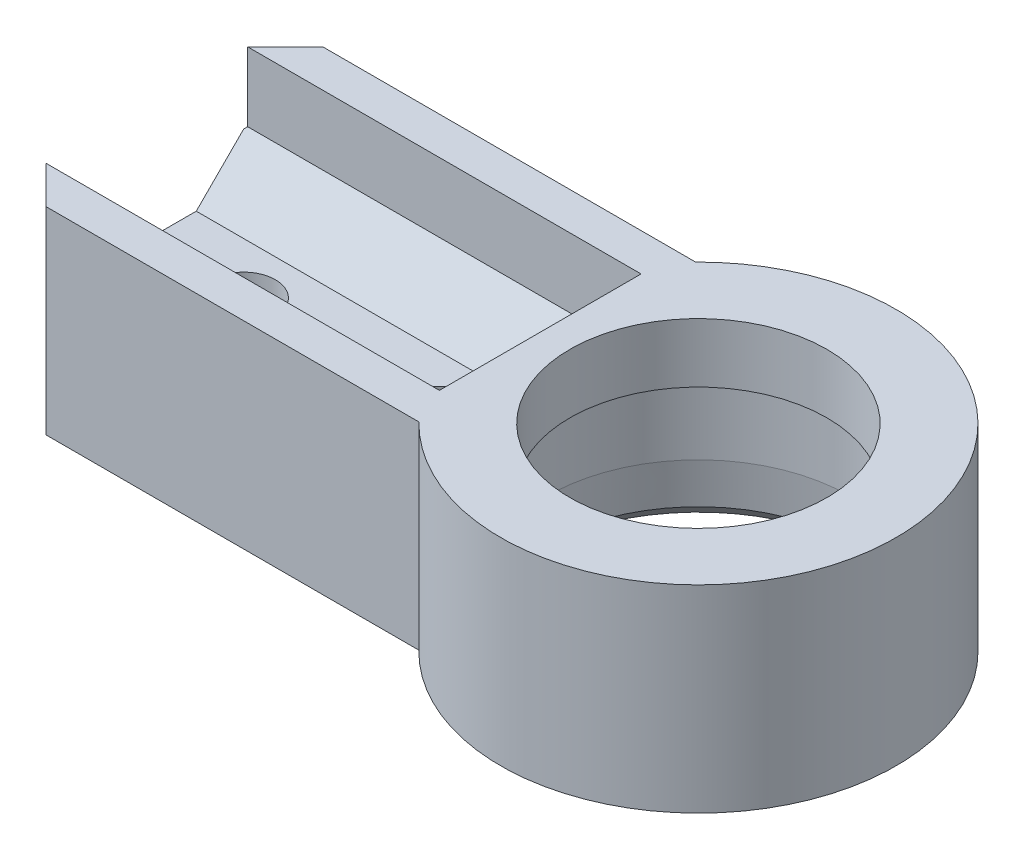
SolidWorks part; units mm, degrees
ref_plane "Plan de face" through (0, 0, 0) normal (0, 0, 1) x (1, 0, 0)
ref_plane "Plan de dessus" through (0, 0, 0) normal (0, 1, 0) x (1, 0, 0)
ref_plane "Plan de droite" through (0, 0, 0) normal (1, 0, 0) x (0, 0, -1)
sketch "Esquisse1" plane through (0, 0, 0) normal (0, 1, 0) x (1, 0, 0)
  line L1 (-28, -7) -> (-7.1414, -7)
  line L2 (-28, -7) -> (-28, 7)
  line L3 (-28, 7) -> (-7.1414, 7)
  line L5 (-28, -7) -> (9.7014, 2.4254) construction
  line L6 (-28, 7) -> (9.7014, -2.4254) construction
  arc A0 (-7.1414, -7) -> (-7.1414, 7) centre (0, 0) ccw
  dimension "D1" = 20
  dimension "D2" = 14
  dimension "D3" = 28
  dimension "D4" = 7
extrude "Boss.-Extru.1" add sketch "Esquisse1" along normal blind 10
sketch "Esquisse2" plane through (-28, 0, 0) normal (-1, 0, 0) x (0, 0, 1)
  line L0 (-7, 10) -> (7, 10) construction
  line L1 (-5.1, 10) -> (5.1, 10)
  line L2 (-5.1, 10) -> (-5.1, 4)
  line L3 (-5.1, 4) -> (5.1, 4)
  line L4 (5.1, 10) -> (5.1, 4)
  line L5 (-7, 0) -> (7, 0) construction
  point P6 (0, 0)
  dimension "D1" = 6
  dimension "D2" = 10.2
  dimension "D3" = 5.1
extrude "Enlèv. mat.-Extru.1" cut sketch "Esquisse2" against normal blind 20
chamfer "Chanfrein1" distance 2.5 angle 45 2 edges at (-18, 4, 5.1) (-18, 4, -5.1)
chamfer "Chanfrein2" distance 1.8 angle 45 3 edges at (-8, 5.25, 3.85) (-8, 4, 0) (-8, 5.25, -3.85)
sketch "Esquisse3" plane through (0, 0, 0) normal (0, -1, 0) x (1, 0, 0)
  circle A0 centre (0, 0) radius 6.5
  dimension "D1" = 13
extrude "Enlèv. mat.-Extru.2" cut sketch "Esquisse3" against normal through all
sketch "Esquisse4" plane through (0, 0, 0) normal (0, -1, 0) x (1, 0, 0)
  circle A0 centre (0, 0) radius 7.65
  dimension "D1" = 15.3
extrude "Enlèv. mat.-Extru.3" cut sketch "Esquisse4" against normal blind 7
chamfer "Chanfrein3" distance 1 angle 45 1 edges at (0, 0, -7.65)
sketch "Esquisse5" plane through (0, 0, 0) normal (0, -1, 0) x (1, 0, 0)
  line L0 (-32.8926, 0) -> (36.0103, 0) construction
  line L2 (-28, -7) -> (-28, 7) construction
  circle A0 centre (-23, 0) radius 1.6
  circle A1 centre (-13, 0) radius 1.6
  dimension "D1" = 3.2
  dimension "D2" = 3.2
  dimension "D7" = 10
  dimension "D8" = 5
extrude "Enlèv. mat.-Extru.4" cut sketch "Esquisse5" against normal blind 7
chamfer "Chanfrein4" distance 2.1 angle 45 2 edges at (-23, 0, -1.6) (-13, 0, -1.6)
chamfer "Chanfrein5" distance 2 angle 45 2 edges at (-28, 5, -7) (-28, 5, 7)
chamfer "Chanfrein6" distance 2 angle 5 1 edges at (0, 1, 7.65)
